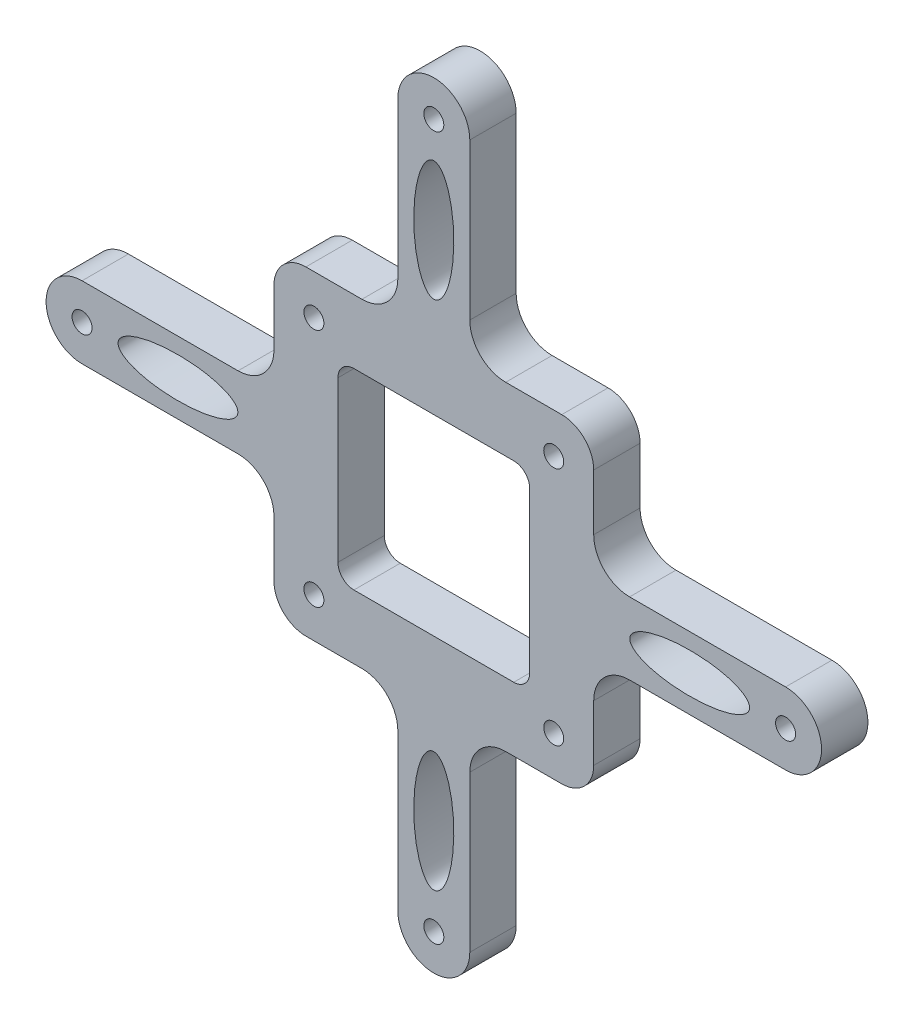
SolidWorks part; units mm, degrees
ref_plane "Front Plane" through (0, 0, 0) normal (0, 0, 1) x (1, 0, 0)
ref_plane "Top Plane" through (0, 0, 0) normal (0, 1, 0) x (1, 0, 0)
ref_plane "Right Plane" through (0, 0, 0) normal (1, 0, 0) x (0, 0, -1)
sketch "Sketch1" plane through (0, 0, 0) normal (0, 0, 1) x (1, 0, 0)
  line L0 (0, 0) -> (-50000, 0) construction
  line L1 (0, 0) -> (0, 56.0888) construction
  line L2 (44.01, -0.01) -> (20, 0) construction
  line L3 (-0.01, -44.01) -> (0, -20) construction
  line L4 (-16, 20) -> (-8.99, 20)
  line L5 (8.99, -20) -> (16, -20)
  line L6 (-20, -20) -> (20, 20) construction
  line L7 (-20, 20) -> (20, -20) construction
  line L8 (4.5, 24.49) -> (4.5, 44)
  line L9 (20, 8.99) -> (20, 16)
  line L10 (-4.5, 24.49) -> (-4.5, 44)
  line L11 (9.9948, -11.9948) -> (-9.9948, -11.9948)
  line L12 (11.9948, -9.9948) -> (11.9948, 9.9948)
  line L13 (9.9948, 11.9948) -> (-9.9948, 11.9948)
  line L14 (-11.9948, -9.9948) -> (-11.9948, 9.9948)
  line L15 (11.9948, -11.9948) -> (-11.9948, 11.9948) construction
  line L16 (11.9948, 11.9948) -> (-11.9948, -11.9948) construction
  line L17 (-0.01, 44.01) -> (0, 20) construction
  line L18 (8.99, 20) -> (16, 20)
  line L19 (24.49, -4.5) -> (44, -4.5)
  line L20 (24.49, 4.5) -> (44, 4.5)
  line L21 (20, -16) -> (20, -8.99)
  line L22 (-4.5, -24.49) -> (-4.5, -44)
  line L23 (4.5, -24.49) -> (4.5, -44)
  line L24 (-16, -20) -> (-8.99, -20)
  line L25 (-44.01, -0.01) -> (-20, 0) construction
  line L26 (-20, -16) -> (-20, -8.99)
  line L27 (-24.49, 4.5) -> (-44, 4.5)
  line L28 (-24.49, -4.5) -> (-44, -4.5)
  line L29 (-20, 8.99) -> (-20, 16)
  circle A0 centre (0, 44) radius 1.25
  circle A1 centre (-15, 15) radius 1.25
  circle A2 centre (15, 15) radius 1.25
  circle A3 centre (15, -15) radius 1.25
  circle A4 centre (-15, -15) radius 1.25
  arc A5 (-4.5, 44) -> (0, 48.5) centre (0, 44) cw
  arc A6 (-4.5, 24.49) -> (-8.99, 20) centre (-8.99, 24.49) cw
  arc A7 (8.99, 20) -> (4.5, 24.49) centre (8.99, 24.49) cw
  arc A8 (0, 48.5) -> (4.5, 44) centre (0, 44) cw
  arc A9 (48.5, 0) -> (44, 4.5) centre (44, 0) ccw
  arc A10 (20, 8.99) -> (24.49, 4.5) centre (24.49, 8.99) ccw
  arc A11 (24.49, -4.5) -> (20, -8.99) centre (24.49, -8.99) ccw
  arc A12 (44, -4.5) -> (48.5, 0) centre (44, 0) ccw
  circle A13 centre (44, 0) radius 1.25
  arc A14 (0, -48.5) -> (4.5, -44) centre (0, -44) ccw
  arc A15 (8.99, -20) -> (4.5, -24.49) centre (8.99, -24.49) ccw
  arc A16 (-4.5, -24.49) -> (-8.99, -20) centre (-8.99, -24.49) ccw
  arc A17 (-4.5, -44) -> (0, -48.5) centre (0, -44) ccw
  circle A18 centre (0, -44) radius 1.25
  circle A19 centre (-44, 0) radius 1.25
  arc A20 (-44, -4.5) -> (-48.5, 0) centre (-44, 0) cw
  arc A21 (-24.49, -4.5) -> (-20, -8.99) centre (-24.49, -8.99) cw
  arc A22 (-20, 8.99) -> (-24.49, 4.5) centre (-24.49, 8.99) cw
  arc A23 (-48.5, 0) -> (-44, 4.5) centre (-44, 0) cw
  arc A24 (-20, -16) -> (-16, -20) centre (-16, -16) ccw
  arc A25 (16, -20) -> (20, -16) centre (16, -16) ccw
  arc A26 (20, 16) -> (16, 20) centre (16, 16) ccw
  arc A27 (-16, 20) -> (-20, 16) centre (-16, 16) ccw
  arc A28 (-11.9948, -9.9948) -> (-9.9948, -11.9948) centre (-9.9948, -9.9948) ccw
  arc A29 (11.9948, -9.9948) -> (9.9948, -11.9948) centre (9.9948, -9.9948) cw
  arc A30 (9.9948, 11.9948) -> (11.9948, 9.9948) centre (9.9948, 9.9948) cw
  arc A31 (-9.9948, 11.9948) -> (-11.9948, 9.9948) centre (-9.9948, 9.9948) ccw
  ellipse E0 centre (-0.005, 32.005) end of major axis (0, 39.5) minor radius 2.505
  ellipse E1 centre (32.005, -0.005) end of major axis (39.5, 0) minor radius 2.505
  ellipse E2 centre (-0.005, -32.005) end of major axis (0, -39.5) minor radius 2.505
  ellipse E3 centre (-32.005, -0.005) end of major axis (-39.5, 0) minor radius 2.505
  point P5 (0, 0)
  point P17 (0, 0)
  point P44 (4.5, 20)
  point P47 (-4.5, 20)
  point P67 (20, -4.5)
  point P68 (20, 4.5)
  point P86 (-4.5, -20)
  point P87 (4.5, -20)
  point P107 (-20, 4.5)
  point P108 (-20, -4.5)
  dimension "D2" = 2.5
  dimension "D7" = 2.5
  dimension "D9" = 4.25
  dimension "D4" = 4
  dimension "D5" = 2
  dimension "D1" = 44
  dimension "D3" = 40
  dimension "D8" = 15
  dimension "D11" = 2
  dimension "D12" = 4.5
extrude "Boss-Extrude1" add sketch "Sketch1" along normal blind 5.8
